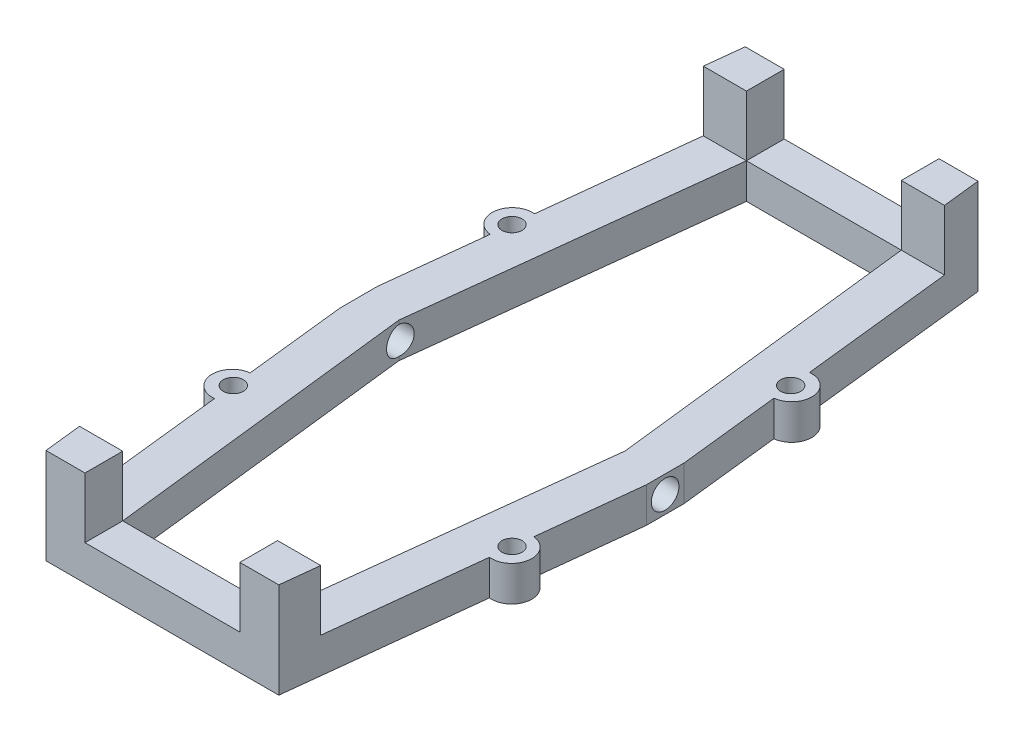
SolidWorks part; units mm, degrees
ref_plane "Front Plane" through (0, 0, 0) normal (0, 0, 1) x (1, 0, 0)
ref_plane "Top Plane" through (0, 0, 0) normal (0, 1, 0) x (1, 0, 0)
ref_plane "Right Plane" through (0, 0, 0) normal (1, 0, 0) x (0, 0, -1)
sketch "Sketch1" plane through (0, 0, 0) normal (0, 1, 0) x (1, 0, 0)
  line L0 (0, 0) -> (0, -34.75) construction
  line L1 (0, -34.75) -> (5.65, 0) construction
  line L2 (5.65, 0) -> (0, 0) construction
  line L3 (5.65, -1.875) -> (5.65, 1.875)
  line L6 (5.65, 1.875) -> (1.9, 1.875)
  line L7 (1.9, 1.875) -> (-1.875, -31)
  line L9 (-1.875, -31) -> (-17.265, -31)
  line L12 (-9.57, 6.0461) -> (-9.57, -44.986) construction
  line L21 (0, -34.75) -> (2, -34.75)
  line L22 (-19.14, -34.75) -> (0, -34.75)
  line L23 (2, -34.75) -> (4.0923, -15.9051)
  line L26 (-24.79, 0) -> (-19.14, 0) construction
  line L27 (-19.14, -34.75) -> (-24.79, 0) construction
  line L28 (-19.14, 0) -> (-19.14, -34.75) construction
  line L30 (-19.14, -34.75) -> (-21.14, -34.75)
  line L31 (-21.04, 1.875) -> (-17.265, -31)
  line L32 (-24.79, 1.875) -> (-21.04, 1.875)
  line L33 (-24.79, -1.875) -> (-24.79, 1.875)
  line L34 (4.5337, -11.9296) -> (5.65, -1.875)
  line L35 (-21.14, -34.75) -> (-23.2323, -15.9051)
  line L36 (-23.6737, -11.9296) -> (-24.79, -1.875)
  arc A0 (4.0923, -15.9051) -> (4.5337, -11.9296) centre (4.313, -13.9174) ccw
  arc A1 (-23.2323, -15.9051) -> (-23.6737, -11.9296) centre (-23.453, -13.9174) cw
  point P7 (5.65, 0)
  point P10 (0, -34.75)
  point P19 (-9.57, -34.75)
  point P20 (-9.57, -34.75)
  point P21 (-9.57, -31)
  point P22 (-9.57, -31)
  point P24 (-19.14, -34.75)
  point P25 (-24.79, 0)
  point P26 (7.9481, -13.85)
  dimension "D11" = 2
  dimension "D1" = 2
  dimension "D2" = 5.65
  dimension "D3" = 3.75
  dimension "D4" = 9.57
  dimension "D5" = 3.75
  dimension "D6" = 7.695
  dimension "D7" = 32.875
  dimension "D8" = 3.75
  dimension "D9" = 33.091
  dimension "D10" = 13.85
  dimension "D12" = 13.9174
extrude "Boss-Extrude1" add sketch "Sketch1" along normal blind 3.5
sketch "Sketch2" plane through (5.65, 0, 0) normal (1, 0, 0) x (0, 0, -1)
  circle A0 centre (0, 1.75) radius 1.375
  dimension "D1" = 2.75
  dimension "D2" = 1.75
extrude "Cut-Extrude1" cut sketch "Sketch2" against normal through all
sketch "Sketch7" plane through (0, 3.5, 0) normal (0, 1, 0) x (1, 0, 0)
  line L8 (-9.57, -20.6242) -> (-9.57, -37.1202) construction
  line L21 (-1.875, -31) -> (-17.265, -31) construction
  line L26 (-1.875, -31) -> (-1.875, -34.75)
  line L27 (-21.14, -34.75) -> (2, -34.75) construction
  line L28 (-1.875, -34.75) -> (2, -34.75)
  line L29 (2, -34.75) -> (2.4163, -31)
  line L30 (2, -34.75) -> (4.0923, -15.9051) construction
  line L31 (2.4163, -31) -> (-1.875, -31)
  line L32 (-21.5563, -31) -> (-17.265, -31)
  line L33 (-21.14, -34.75) -> (-21.5563, -31)
  line L34 (-17.265, -34.75) -> (-21.14, -34.75)
  line L35 (-17.265, -31) -> (-17.265, -34.75)
  point P14 (-9.57, -31)
extrude "Boss-Extrude5" add sketch "Sketch7" along normal blind 6
mirror "Mirror46" about plane through (0, 0, 0) normal (0, 0, 1) of "Boss-Extrude5", "Cut-Extrude1", "Boss-Extrude1"
sketch "Sketch8" plane through (0, 0, 0) normal (0, 1, 0) x (1, 0, 0)
  line L0 (5.65, -1.875) -> (5.65, 1.875) construction
  line L3 (-24.79, 1.875) -> (-24.79, -1.875) construction
  line L5 (-23.42, -13.85) -> (4.28, -13.85) construction
  line L6 (-23.42, -13.85) -> (-23.42, 13.85) construction
  line L7 (-23.42, 13.85) -> (4.28, 13.85) construction
  line L8 (4.28, -13.85) -> (4.28, 13.85) construction
  line L9 (-23.42, -13.85) -> (4.28, 13.85) construction
  line L10 (-23.42, 13.85) -> (4.28, -13.85) construction
  point P4 (5.65, 0)
  point P9 (-9.57, 0)
  dimension "D1" = 27.7
  dimension "D2" = 15.22
  dimension "D3" = 15.22
  dimension "D4" = 13.85
sketch "Sketch9" plane through (0, 3.5, 0) normal (0, 1, 0) x (1, 0, 0)
  circle A0 centre (4.28, 13.85) radius 1
  circle A1 centre (-23.42, 13.85) radius 1
  circle A2 centre (-23.42, -13.85) radius 1
  circle A3 centre (4.28, -13.85) radius 1
  dimension "D1" = 2
extrude "Cut-Extrude2" cut sketch "Sketch9" against normal blind 10
